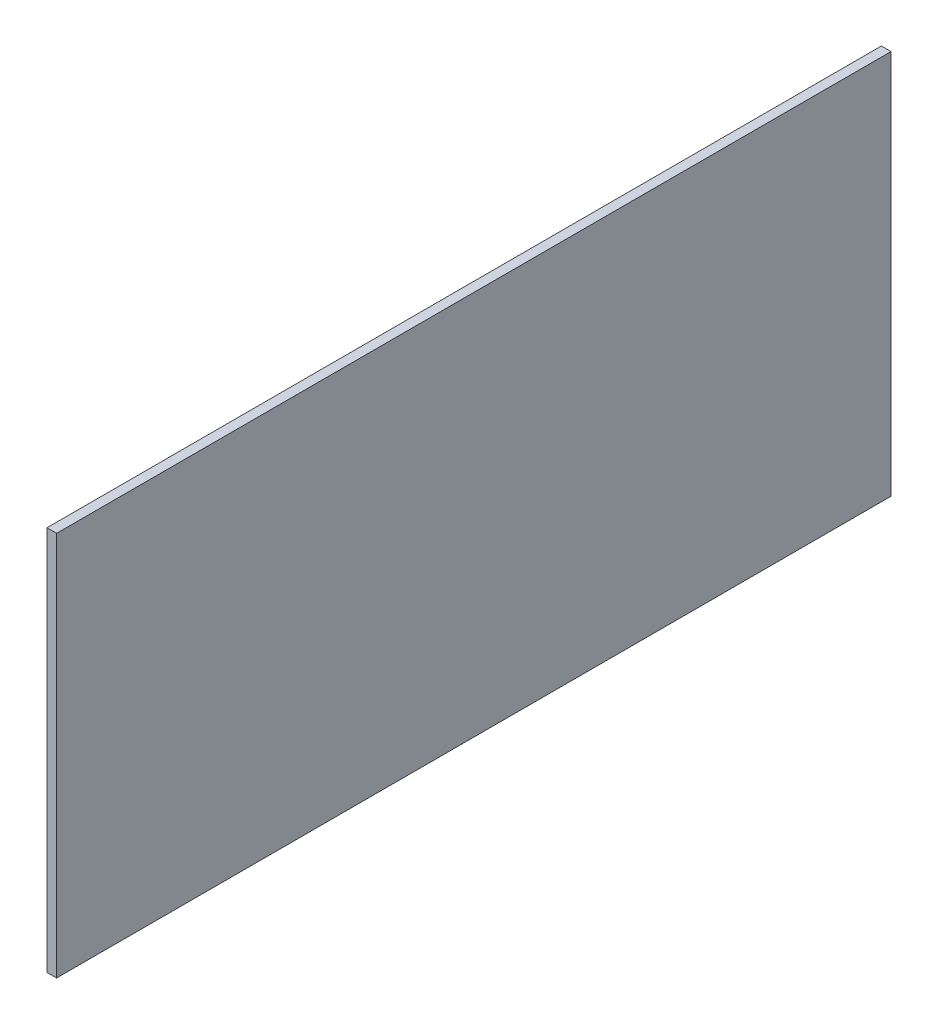
SolidWorks part; units mm, degrees
ref_plane "Front Plane" through (0, 0, 0) normal (1, 0, 0) x (0, 1, 0)
ref_plane "Top Plane" through (0, 0, 0) normal (0, 0, 1) x (0, 1, 0)
ref_plane "Right Plane" through (0, 0, 0) normal (0, 1, 0) x (-1, 0, 0)
sketch "Sketch1" plane through (0, 0, 0) normal (1, 0, 0) x (0, 1, 0)
  line L1 (-300, -650) -> (300, -650)
  line L2 (-300, -650) -> (-300, 650)
  line L3 (-300, 650) -> (300, 650)
  line L4 (300, -650) -> (300, 650)
  line L5 (-300, -650) -> (300, 650) construction
  line L6 (-300, 650) -> (300, -650) construction
  point P0 (0, 0)
  dimension "D1" = 1300
  dimension "D2" = 600
extrude "Boss-Extrude1" add sketch "Sketch1" along normal blind 15
sketch "Sketch2" plane through (15, 0, 0) normal (1, 0, 0) x (0, 1, 0)
  line L0 (-300, -650) -> (300, -650) construction
  line L1 (-135, -390) -> (135, -390)
  line L2 (-135, -390) -> (-135, -590)
  line L3 (-135, -590) -> (135, -590)
  line L4 (135, -390) -> (135, -590)
  line L5 (-300, 650) -> (-300, -650) construction
  line L6 (300, -650) -> (300, 650) construction
  line L7 (30, -150) -> (230, -150)
  line L8 (30, -150) -> (30, -300)
  line L9 (30, -300) -> (230, -300)
  line L10 (230, -150) -> (230, -300)
  line L11 (-177.5736, 465.1472) -> (-135.1472, 507.5736) construction
  line L12 (-174.55, 123.4) -> (179.55, 123.4)
  line L13 (-174.55, 123.4) -> (-174.55, 0)
  line L14 (-174.55, 0) -> (179.55, 0)
  line L15 (179.55, 123.4) -> (179.55, 0)
  line L16 (-174.55, 0) -> (-194.55, 0)
  line L17 (-174.55, 0) -> (-174.55, -20)
  line L18 (-174.55, -20) -> (-194.55, -20)
  line L19 (-194.55, 0) -> (-194.55, -20)
  line L20 (-174.55, 123.4) -> (-194.55, 123.4)
  line L21 (-174.55, 123.4) -> (-174.55, 143.4)
  line L22 (-174.55, 143.4) -> (-194.55, 143.4)
  line L23 (-194.55, 123.4) -> (-194.55, 143.4)
  line L24 (179.55, 123.4) -> (199.55, 123.4)
  line L25 (179.55, 123.4) -> (179.55, 143.4)
  line L26 (179.55, 143.4) -> (199.55, 143.4)
  line L27 (199.55, 123.4) -> (199.55, 143.4)
  line L28 (179.55, 0) -> (199.55, 0)
  line L29 (179.55, 0) -> (179.55, -20)
  line L30 (179.55, -20) -> (199.55, -20)
  line L31 (199.55, 0) -> (199.55, -20)
  line L32 (-49, 251.9) -> (54, 251.9)
  line L33 (-49, 251.9) -> (-49, 173.4)
  line L34 (-49, 173.4) -> (54, 173.4)
  line L35 (54, 251.9) -> (54, 173.4)
  line L72 (30, 330) -> (70, 330) construction
  line L74 (30, 330) -> (30, 370) construction
  line L75 (30, 370) -> (70, 370) construction
  line L76 (70, 330) -> (70, 370) construction
  line L77 (30, 330) -> (70, 370) construction
  line L78 (30, 370) -> (70, 330) construction
  line L79 (30, 370) -> (40, 370)
  line L80 (30, 370) -> (30, 360)
  line L81 (30, 360) -> (40, 360)
  line L82 (40, 370) -> (40, 360)
  line L83 (30, 330) -> (40, 330)
  line L84 (30, 330) -> (30, 340)
  line L85 (30, 340) -> (40, 340)
  line L86 (40, 330) -> (40, 340)
  line L87 (70, 330) -> (60, 330)
  line L88 (70, 330) -> (70, 340)
  line L89 (70, 340) -> (60, 340)
  line L90 (60, 330) -> (60, 340)
  line L91 (70, 370) -> (60, 370)
  line L92 (70, 370) -> (70, 360)
  line L93 (70, 360) -> (60, 360)
  line L94 (60, 370) -> (60, 360)
  line L95 (270, 330) -> (230, 330) construction
  line L96 (270, 330) -> (270, 370) construction
  line L97 (270, 370) -> (230, 370) construction
  line L98 (230, 330) -> (230, 370) construction
  line L99 (270, 330) -> (230, 370) construction
  line L100 (270, 370) -> (230, 330) construction
  line L101 (230, 370) -> (240, 370)
  line L102 (230, 370) -> (230, 360)
  line L103 (230, 360) -> (240, 360)
  line L104 (240, 370) -> (240, 360)
  line L105 (230, 330) -> (240, 330)
  line L106 (230, 330) -> (230, 340)
  line L107 (230, 340) -> (240, 340)
  line L108 (240, 330) -> (240, 340)
  line L109 (270, 330) -> (260, 330)
  line L110 (270, 330) -> (270, 340)
  line L111 (270, 340) -> (260, 340)
  line L112 (260, 330) -> (260, 340)
  line L113 (270, 370) -> (260, 370)
  line L114 (270, 370) -> (270, 360)
  line L115 (270, 360) -> (260, 360)
  line L116 (260, 370) -> (260, 360)
  line L117 (-177.5736, 465.1472) -> (-220, 507.5736) construction
  line L118 (-135.1472, 507.5736) -> (-177.5736, 550) construction
  line L119 (-220, 507.5736) -> (-177.5736, 550) construction
  line L120 (300, 650) -> (-300, 650) construction
  line L122 (-185, -117.5) -> (-169.3, -117.5)
  line L123 (-185, -117.5) -> (-185, -125)
  line L124 (-185, -125) -> (-169.3, -125)
  line L125 (-169.3, -117.5) -> (-169.3, -125)
  circle A0 centre (-175, -225) radius 19
  circle A3 centre (50, 350) radius 9.5
  circle A4 centre (250, 350) radius 9.5
  circle A5 centre (-177.5736, 550) radius 15
  circle A6 centre (-220, 507.5736) radius 15
  circle A7 centre (-177.5736, 465.1472) radius 15
  circle A8 centre (-135.1472, 507.5736) radius 15
  circle A9 centre (-200, 330) radius 20
  circle A10 centre (60, 590) radius 5
  circle A11 centre (140, 590) radius 5
  circle A12 centre (220, 590) radius 5
  point P20 (-174.55, 61.7)
  point P33 (-184.55, 123.4)
  point P34 (-174.55, 133.4)
  dimension "D9" = 38
  dimension "D16" = 20
  dimension "D22" = 125
  dimension "D23" = 425
  dimension "D28" = 19
  dimension "D29" = 19
  dimension "D47" = 60
  dimension "D32" = 10
  dimension "D42" = 1000
  dimension "D43" = 1000
  dimension "D44" = 50
  dimension "D45" = 200
  dimension "D51" = 30
  dimension "D52" = 30
  dimension "D53" = 30
  dimension "D54" = 30
  dimension "D59" = 40
  dimension "D60" = 100
  dimension "D61" = 320
  dimension "D62" = 10
  dimension "D63" = 10
  dimension "D64" = 10
  dimension "D65" = 60
  dimension "D66" = 60
  dimension "D67" = 60
  dimension "D68" = 80
  dimension "D69" = 80
  dimension "D70" = 80
  dimension "D1" = 200
  dimension "D2" = 270
  dimension "D3" = 60
  dimension "D4" = 165
  dimension "D5" = 150
  dimension "D6" = 200
  dimension "D7" = 70
  dimension "D8" = 350
  dimension "D10" = 123.4
  dimension "D11" = 354.1
  dimension "D12" = 125.45
  dimension "D13" = 20
  dimension "D14" = 20
  dimension "D15" = 650
  dimension "D17" = 20
  dimension "D18" = 20
  dimension "D19" = 20
  dimension "D20" = 20
  dimension "D21" = 20
  dimension "D24" = 103
  dimension "D25" = 78.5
  dimension "D26" = 50
  dimension "D27" = 125.55
  dimension "D30" = 40
  dimension "D31" = 40
  dimension "D33" = 10
  dimension "D34" = 10
  dimension "D35" = 10
  dimension "D36" = 40
  dimension "D37" = 40
  dimension "D38" = 10
  dimension "D39" = 10
  dimension "D40" = 10
  dimension "D41" = 10
  dimension "D46" = 60
  dimension "D48" = 80
  dimension "D49" = 100
  dimension "D50" = 42.4264
  dimension "D55" = 7.5
  dimension "D56" = 15.7
  dimension "D57" = 115
  dimension "D58" = 525
